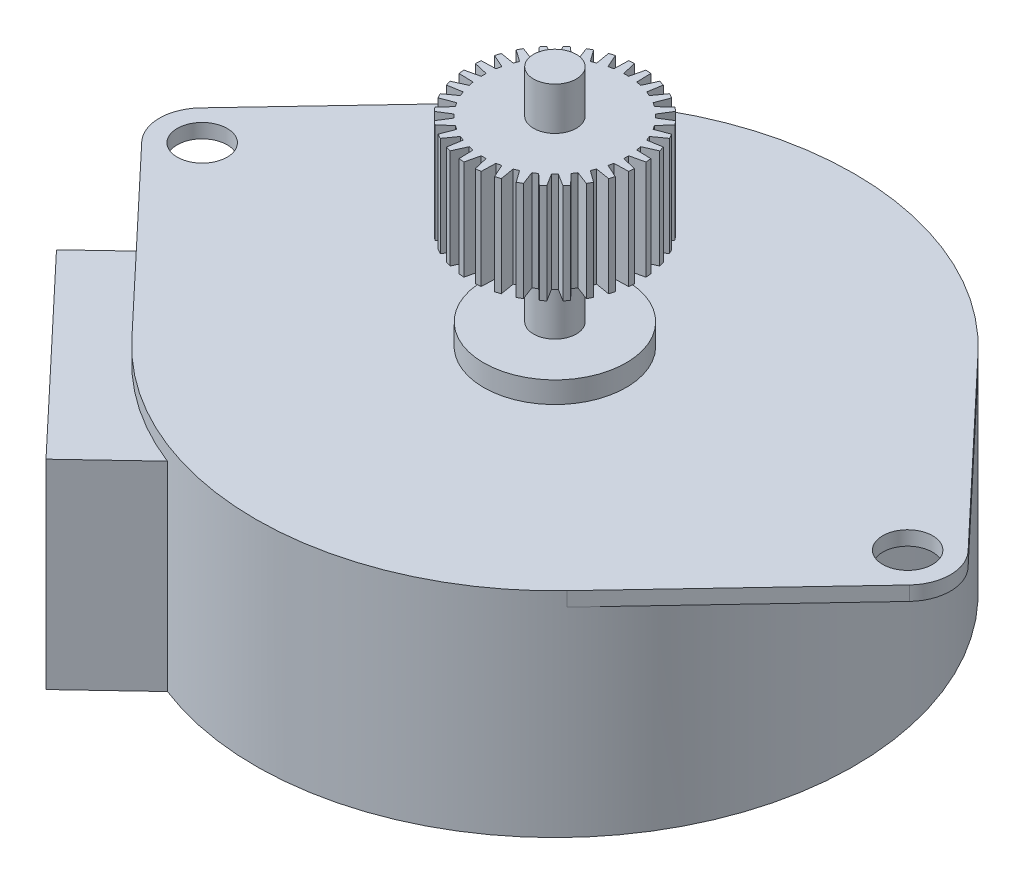
SolidWorks part; units mm, degrees
ref_plane "정면" through (0, 0, 0) normal (0, 0, 1) x (1, 0, 0)
ref_plane "윗면" through (0, 0, 0) normal (0, 1, 0) x (1, 0, 0)
ref_plane "우측면" through (0, 0, 0) normal (1, 0, 0) x (0, 0, -1)
sketch "스케치1" plane through (0, 0, 0) normal (0, 1, 0) x (1, 0, 0)
  line L0 (0, 0) -> (24.75, 0) construction
  line L1 (0, 0) -> (-24.75, 0) construction
  line L2 (15.2727, 14.4133) -> (26.9318, 2.059)
  line L3 (26.9318, -2.059) -> (15.2727, -14.4133)
  line L4 (-15.2727, -14.4133) -> (-26.9318, -2.059)
  line L5 (-26.9318, 2.059) -> (-15.2727, 14.4133)
  arc A0 (26.9318, -2.059) -> (26.9318, 2.059) centre (24.75, 0) ccw
  arc A1 (-26.9318, 2.059) -> (-26.9318, -2.059) centre (-24.75, 0) ccw
  arc A2 (-15.2727, -14.4133) -> (15.2727, -14.4133) centre (0, 0) ccw
  arc A3 (15.2727, 14.4133) -> (-15.2727, 14.4133) centre (0, 0) ccw
  dimension "D2" = 6
  dimension "D3" = 42
  dimension "D1" = 49.5
extrude "보스-돌출1" add sketch "스케치1" along normal blind 1
sketch "스케치2" plane through (0, 0, 0) normal (0, -1, 0) x (1, 0, 0)
  circle A0 centre (0, 0) radius 21
extrude "보스-돌출2" add sketch "스케치2" along normal blind 14
sketch "스케치3" plane through (-15.2727, 0, 14.4133) normal (-0.7273, 0, 0.6863) x (0.6863, 0, 0.7273)
  line L1 (-9, 0) -> (9, 0)
  line L2 (-9, 0) -> (-9, -14)
  line L3 (-9, -14) -> (9, -14)
  line L4 (9, 0) -> (9, -14)
  line L5 (-21, -14) -> (21, -14) construction
  line L6 (-9, -7) -> (0, -7) construction
  line L7 (0, -7) -> (0, 1.2821) construction
  line L8 (0, -7) -> (9, -7) construction
  line L9 (-16.9871, 0) -> (0, 0) construction
  dimension "D1" = 18
extrude "보스-돌출3" add sketch "스케치3" along normal blind 4 and the other way blind 14
sketch "스케치4" plane through (0, 1, 0) normal (0, 1, 0) x (1, 0, 0)
  circle A0 centre (24.75, 0) radius 1.75
  circle A1 centre (-24.75, 0) radius 1.75
  dimension "D1" = 3.5
extrude "컷-돌출1" cut sketch "스케치4" against normal blind 4
sketch "스케치5" plane through (0, 1, 0) normal (0, 1, 0) x (1, 0, 0)
  circle A0 centre (0, 0) radius 5
extrude "보스-돌출4" add sketch "스케치5" along normal blind 1.5
sketch "스케치6" plane through (0, 2.5, 0) normal (0, 1, 0) x (1, 0, 0)
  circle A0 centre (0, 0) radius 1.5
  dimension "D1" = 3
extrude "보스-돌출5" add sketch "스케치6" along normal blind 15.5
ref_plane "평면1" through (0, 15, 0) normal (0, 1, 0) x (1, 0, 0)
sketch "스케치8" plane through (0, 15, 0) normal (0, 1, 0) x (1, 0, 0)
  circle A0 centre (0, 0) radius 6
  dimension "D1" = 12
extrude "보스-돌출6" add sketch "스케치8" against normal blind 7 separate body
sketch "스케치9" plane through (0, 15, 0) normal (0, 1, 0) x (1, 0, 0)
  line L0 (0, 0) -> (0, 6) construction
  line L1 (0, 5) -> (0.1733, 5)
  line L2 (0.1733, 5) -> (0.4, 5.9867)
  line L3 (0.4, 5.9867) -> (0, 6.4539)
  line L4 (0, 6.4539) -> (-0.4, 5.9867)
  line L5 (-0.4, 5.9867) -> (-0.1733, 5)
  line L6 (-0.1733, 5) -> (0, 5)
  circle A0 centre (0, 0) radius 6 construction
  dimension "D1" = 1
  dimension "D2" = 0.8
extrude "컷-돌출2" cut sketch "스케치9" against normal blind 7
pattern_circular "원형 패턴1" count 32 over 360 about axis through (0, 0, 0) along (0, 1, 0) of "컷-돌출2"
